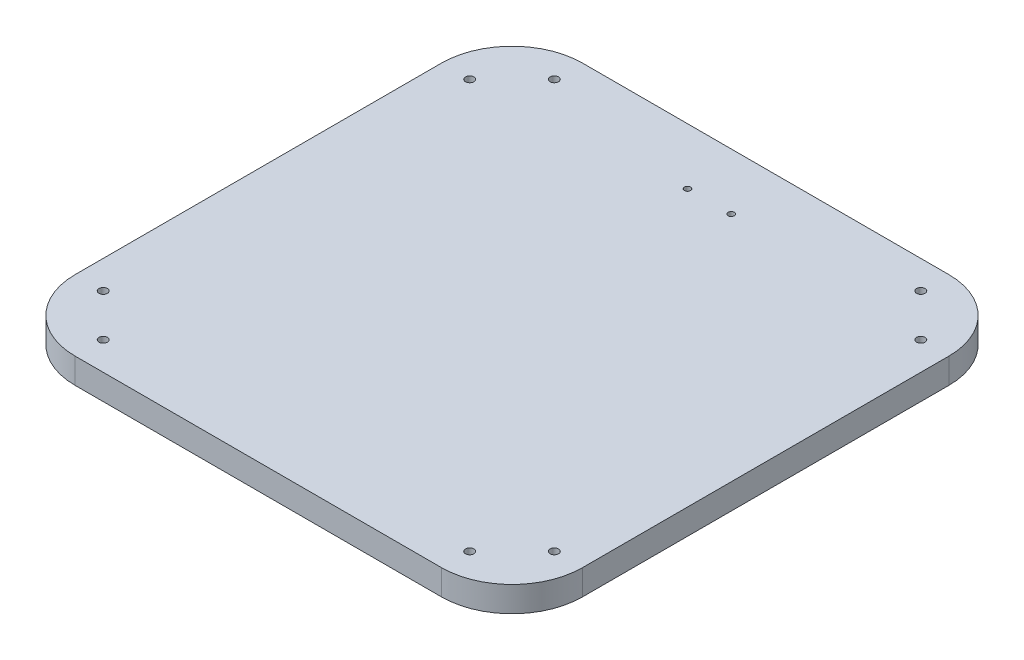
SolidWorks part; units mm, degrees
ref_plane "Front Plane" through (0, 0, 0) normal (0, 0, 1) x (1, 0, 0)
ref_plane "Top Plane" through (0, 0, 0) normal (0, 1, 0) x (1, 0, 0)
ref_plane "Right Plane" through (0, 0, 0) normal (1, 0, 0) x (0, 0, -1)
sketch "Sketch1" plane through (0, 0, 0) normal (0, 1, 0) x (1, 0, 0)
  line L1 (-65, -90) -> (65, -90)
  line L2 (-90, -65) -> (-90, 65)
  line L3 (-65, 90) -> (65, 90)
  line L4 (90, -65) -> (90, 65)
  arc A0 (-90, 65) -> (-65, 90) centre (-65, 65) cw
  arc A1 (65, 90) -> (90, 65) centre (65, 65) cw
  arc A2 (90, -65) -> (65, -90) centre (65, -65) cw
  arc A3 (-65, -90) -> (-90, -65) centre (-65, -65) cw
  point P4 (-90, 0)
  point P6 (0, 90)
  dimension "D3" = 25
  dimension "D1" = 180
  dimension "D2" = 180
extrude "Boss-Extrude1" add sketch "Sketch1" along normal blind 9
sketch "Sketch2" plane through (0, 9, 0) normal (0, 1, 0) x (1, 0, 0)
  line L0 (-7.747, 70) -> (7.747, 70) construction
  line L1 (0, 90) -> (0, 70) construction
  line L2 (-65, 90) -> (65, 90) construction
  circle A1 centre (-7.747, 70) radius 1.09
  circle A2 centre (7.747, 70) radius 1.09
  dimension "D3" = 2.18
  dimension "D1" = 15.494
  dimension "D2" = 20
extrude "Cut-Extrude1" cut sketch "Sketch2" against normal through all
sketch "Sketch3" plane through (0, 9, 0) normal (0, 1, 0) x (1, 0, 0)
  line L0 (-65, 90) -> (-65, -90) construction
  line L1 (65, 90) -> (65, -90) construction
  line L2 (-90, 65) -> (90, 65) construction
  line L3 (-90, -65) -> (90, -65) construction
  circle A0 centre (-65, 80) radius 1.5
  circle A1 centre (-80, 65) radius 1.5
  circle A2 centre (80, 65) radius 1.5
  circle A3 centre (80, -65) radius 1.5
  circle A4 centre (65, 80) radius 1.5
  circle A5 centre (65, -80) radius 1.5
  circle A6 centre (-65, -80) radius 1.5
  circle A7 centre (-80, -65) radius 1.5
  dimension "D1" = 3
  dimension "D2" = 15
  dimension "D3" = 15
  dimension "D4" = 15
  dimension "D5" = 15
  dimension "D6" = 15
  dimension "D7" = 15
  dimension "D8" = 15
  dimension "D9" = 15
extrude "Cut-Extrude2" cut sketch "Sketch3" against normal through all
